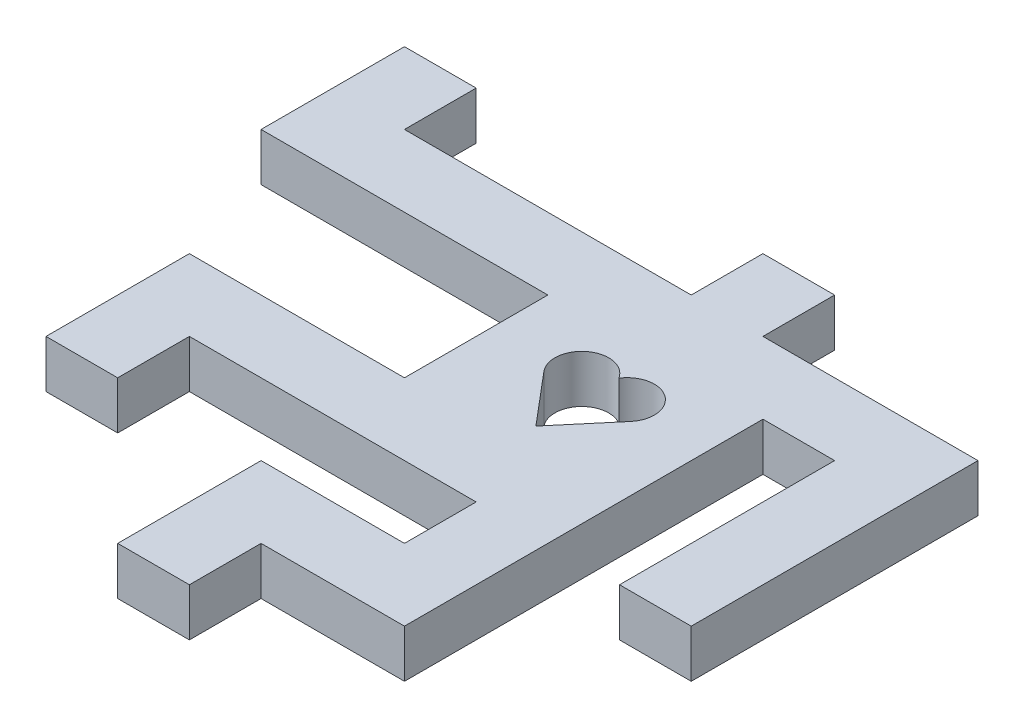
SolidWorks part; units mm, degrees
ref_plane "Front Plane" through (0, 0, 0) normal (0, 0, 1) x (1, 0, 0)
ref_plane "Top Plane" through (0, 0, 0) normal (0, 1, 0) x (1, 0, 0)
ref_plane "Right Plane" through (0, 0, 0) normal (1, 0, 0) x (0, 0, -1)
sketch "Sketch1" plane through (0, 0, 0) normal (0, 1, 0) x (1, 0, 0)
  line L0 (11.25, 15) -> (26.25, 15)
  line L1 (-11.25, 15) -> (11.25, 15)
  line L2 (-11.25, 15) -> (-11.25, -15)
  line L3 (-11.25, -15) -> (11.25, -15)
  line L4 (11.25, 15) -> (11.25, -15)
  line L5 (-11.25, 15) -> (11.25, -15) construction
  line L6 (-11.25, -15) -> (11.25, 15) construction
  line L7 (-3.75, 15) -> (3.75, 15)
  line L8 (-3.75, 15) -> (-3.75, 22.5)
  line L9 (-3.75, 22.5) -> (3.75, 22.5)
  line L10 (3.75, 15) -> (3.75, 22.5)
  line L11 (26.25, 15) -> (26.25, -15)
  line L12 (26.25, -15) -> (18.75, -15)
  line L13 (18.75, -15) -> (18.75, 7.5)
  line L14 (18.75, 7.5) -> (11.25, 7.5)
  line L15 (-11.25, 15) -> (-33.75, 15)
  line L16 (-33.75, 15) -> (-33.75, 22.5)
  line L17 (-33.75, 22.5) -> (-41.25, 22.5)
  line L18 (-41.25, 22.5) -> (-41.25, 7.5)
  line L19 (-41.25, 7.5) -> (-11.25, 7.5)
  line L20 (11.25, -15) -> (11.25, -30)
  line L21 (11.25, -30) -> (-3.75, -30)
  line L22 (-3.75, -30) -> (-3.75, -37.5)
  line L23 (-3.75, -37.5) -> (-11.25, -37.5)
  line L24 (-11.25, -37.5) -> (-11.25, -22.5)
  line L25 (-11.25, -22.5) -> (3.75, -22.5)
  line L26 (3.75, -22.5) -> (3.75, -15)
  line L27 (-11.25, -15) -> (-26.25, -15)
  line L28 (-26.25, -15) -> (-26.25, -22.5)
  line L29 (-26.25, -22.5) -> (-33.75, -22.5)
  line L30 (-33.75, -22.5) -> (-33.75, -7.5)
  line L31 (-33.75, -7.5) -> (-11.25, -7.5)
  point P0 (0, 0)
  dimension "D1" = 30
  dimension "D2" = 22.5
  dimension "D3" = 7.5
  dimension "D4" = 7.5
  dimension "D5" = 7.5
  dimension "D6" = 22.5
  dimension "D7" = 30
  dimension "D8" = 15
  dimension "D9" = 15
  dimension "D10" = 30
  dimension "D11" = 7.5
  dimension "D12" = 7.5
  dimension "D13" = 15
  dimension "D14" = 15
  dimension "D15" = 15
  dimension "D16" = 7.5
  dimension "D17" = 7.5
  dimension "D18" = 7.5
  dimension "D19" = 22.5
  dimension "D20" = 15
  dimension "D21" = 15
  dimension "D22" = 7.5
extrude "Boss-Extrude1" add sketch "Sketch1" along normal blind 5 contours L18 L19 L2 L15 L16 L17 | L31 L30 L29 L28 L27 L2 | L4 L1 L2 L3 | L26 L25 L24 L23 L22 L21 L20 L3 | L1 L10 L9 L8 | L14 L13 L12 L11 L0 L4
sketch "Sketch2" plane through (0, 5, 0) normal (0, 1, 0) x (1, 0, 0)
  line L0 (-11.25, 7.5) -> (11.25, 7.5) construction
  line L1 (-11.25, -7.5) -> (11.25, -7.5) construction
  line L2 (11.25, 7.5) -> (11.25, -30) construction
  line L3 (0, 7.5) -> (0, -7.5) construction
  line L4 (0, -5) -> (4.5349, 0.3719)
  line L6 (-11.25, 0) -> (11.25, 0) construction
  line L7 (-11.25, 7.5) -> (-11.25, -7.5) construction
  line L8 (2.3851, 5) -> (0, 5) construction
  line L9 (0, -5) -> (-4.5349, 0.3719)
  arc A1 (4.5349, 0.3719) -> (0, 3.6786) centre (2.3851, 2.1867) ccw
  arc A2 (-4.5349, 0.3719) -> (0, 3.6786) centre (-2.3851, 2.1867) cw
  dimension "D4" = 2.5
  dimension "D1" = 2.5
extrude "Cut-Extrude3" cut sketch "Sketch2" against normal blind 10
equation "\"Square Width\" = 7.5mm"
equation "\"Square Height\"= 7.5mm"
equation "\"Tolerance\"= 1mm"
equation "\"Block Height\" = 5mm"
equation "\"Base Height\"= 10mm"
equation "\"D1@Sketch1\"=\"Square Height\"*4"
equation "\"D2@Sketch1\"=\"Square Width\"*3"
equation "\"D3@Sketch1\"=\"Square Width\""
equation "\"D4@Sketch1\"=\"Square Height\""
equation "\"D5@Sketch1\"=\"Square Width\""
equation "\"D6@Sketch1\"=\"Square Width\"*3"
equation "\"D7@Sketch1\"=\"Square Width\"*4"
equation "\"D8@Sketch1\"=\"Square Height\"*2"
equation "\"D9@Sketch1\"=\"Square Width\"*2"
equation "\"D10@Sketch1\"=\"Square Height\"*4"
equation "\"D11@Sketch1\"=\"Square Width\""
equation "\"D12@Sketch1\"=\"Square Height\""
equation "\"D13@Sketch1\"=\"Square Height\"*2"
equation "\"D14@Sketch1\"=\"Square Width\"*2"
equation "\"D15@Sketch1\"=\"Square Height\"*2"
equation "\"D16@Sketch1\"=\"Square Width\""
equation "\"D17@Sketch1\"=\"Square Height\""
equation "\"D18@Sketch1\"=\"Square Width\""
equation "\"D19@Sketch1\"=\"Square Width\"*3"
equation "\"D20@Sketch1\"=\"Square Height\"*2"
equation "\"D21@Sketch1\"=\"Square Width\"*2"
equation "\"D22@Sketch1\"=\"Square Height\""
equation "\"D1@Boss-Extrude1\"=\"Block Height\""
equation "\"D4@Sketch2\"=\"Square Height\"/3"
equation "\"D1@Sketch2\"=\"Square Height\"/3"
